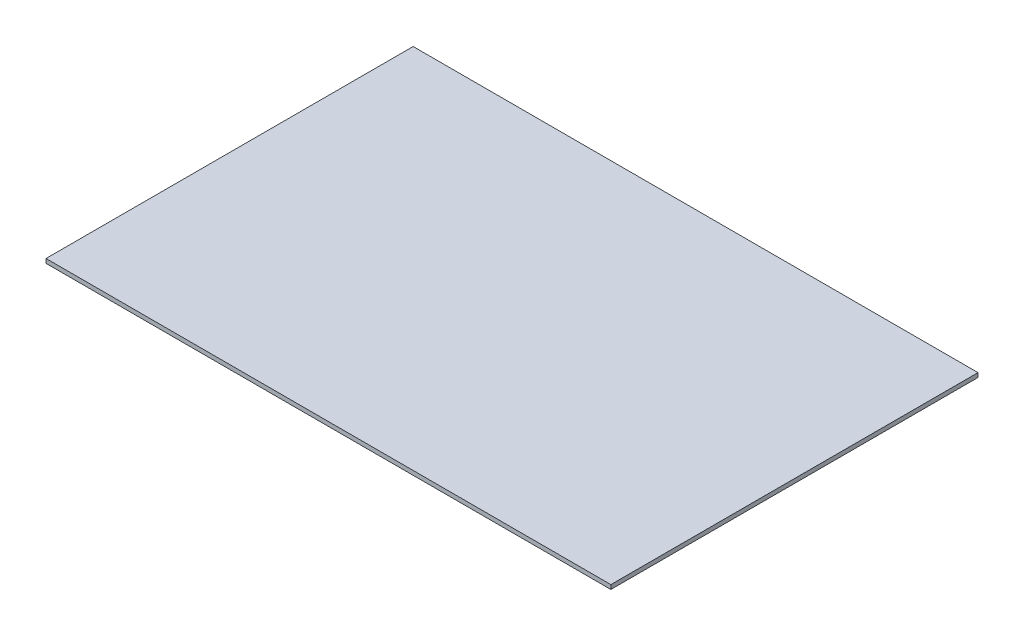
SolidWorks part; units mm, degrees
material "FR-4"
ref_plane "Спереди" through (0, 0, 0) normal (0, 0, 1) x (1, 0, 0)
ref_plane "Сверху" through (0, 0, 0) normal (0, 1, 0) x (1, 0, 0)
ref_plane "Справа" through (0, 0, 0) normal (1, 0, 0) x (0, 0, -1)
other "Configuration Table"
sketch "Эскиз1" plane through (0, 0, 0) normal (0, 1, 0) x (1, 0, 0)
  line L1 (0, 130) -> (200, 130)
  line L2 (0, 130) -> (0, 0)
  line L3 (0, 0) -> (200, 0)
  line L4 (200, 130) -> (200, 0)
  dimension "D1" = 200
  dimension "D2" = 130
extrude "Бобышка-Вытянуть1" add sketch "Эскиз1" along normal blind 1.5
